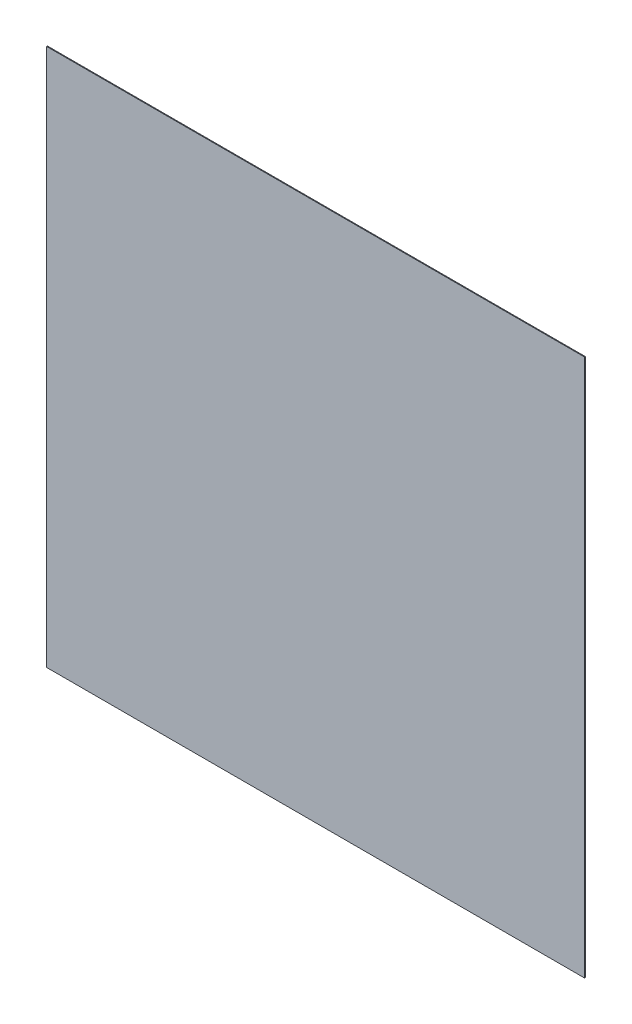
SolidWorks part; units mm, degrees
ref_plane "Front Plane" through (0, 0, 0) normal (0, 0, 1) x (1, 0, 0)
ref_plane "Top Plane" through (0, 0, 0) normal (0, 1, 0) x (1, 0, 0)
ref_plane "Right Plane" through (0, 0, 0) normal (1, 0, 0) x (0, 0, -1)
sketch "Sketch1" plane through (0, 0, 0) normal (0, 0, 1) x (1, 0, 0)
  line L1 (-10, 10) -> (10, 10)
  line L2 (-10, 10) -> (-10, -10)
  line L3 (-10, -10) -> (10, -10)
  line L4 (10, 10) -> (10, -10)
extrude "Boss-Extrude1" add sketch "Sketch1" along normal blind 0.03
